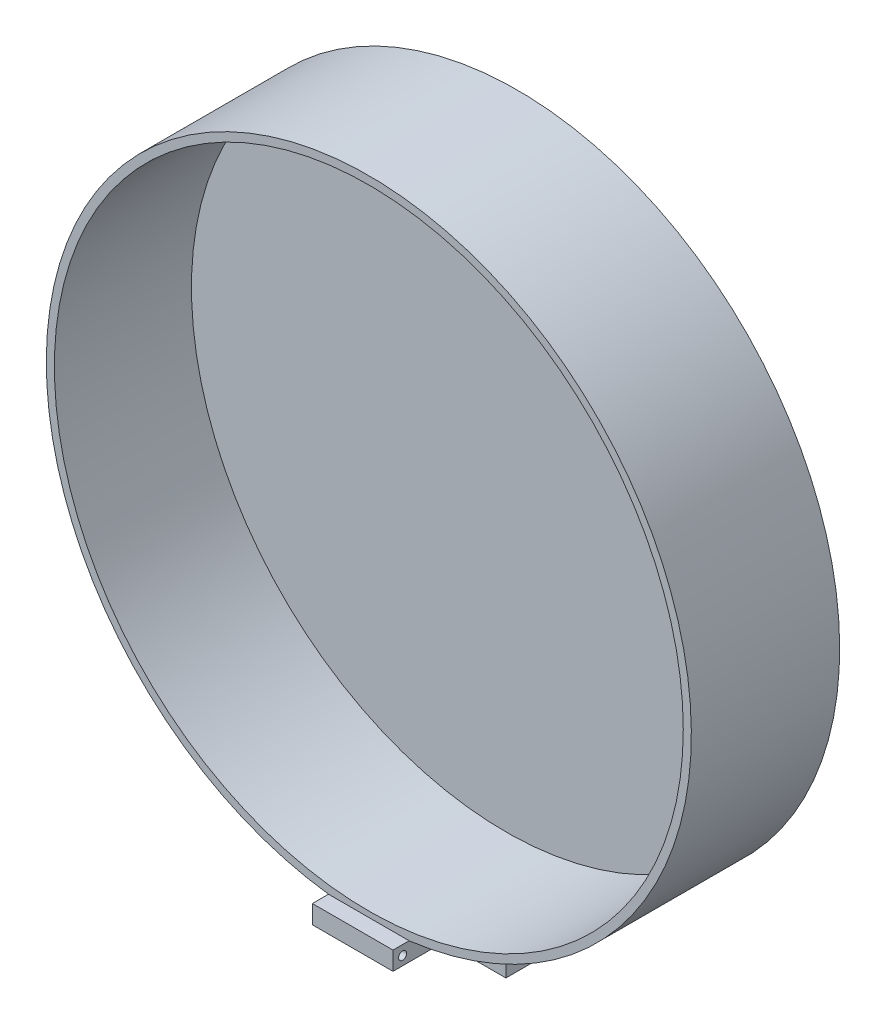
SolidWorks part; units mm, degrees
ref_plane "Front Plane" through (0, 0, 0) normal (0, 0, 1) x (1, 0, 0)
ref_plane "Top Plane" through (0, 0, 0) normal (0, 1, 0) x (1, 0, 0)
ref_plane "Right Plane" through (0, 0, 0) normal (1, 0, 0) x (0, 0, -1)
sketch "Sketch1" plane through (0, 0, 0) normal (0, 0, 1) x (1, 0, 0)
  line L0 (0, 0) -> (12.7, 0)
  line L1 (12.7, 0) -> (12.7, 12.7)
  line L2 (0, 0) -> (0, 12.7)
  arc A0 (0, 12.7) -> (12.7, 12.7) centre (6.35, 63.1016) cw
  dimension "D4" = 50.8
  dimension "D1" = 12.7
  dimension "D2" = 12.7
  dimension "D3" = 12.7
extrude "Boss-Extrude1" add sketch "Sketch1" along normal blind 23.368
sketch "Sketch4" plane through (0, 0, 23.368) normal (0, 0, 1) x (1, 0, 0)
  line L0 (-44.45, 63.1016) -> (57.15, 63.1016) construction
  arc A0 (12.7, 12.7) -> (0, 12.7) centre (6.35, 63.1016) ccw construction
  circle A1 centre (6.35, 63.1016) radius 49.53
  dimension "D1" = 99.06
extrude "Cut-Extrude1" cut sketch "Sketch4" against normal blind 21.59
sketch "Sketch5" plane through (0, 0, 23.368) normal (0, 0, 1) x (1, 0, 0)
  line L0 (0, 0) -> (12.7, 0)
  line L1 (12.7, 0) -> (12.7, 12.7)
  line L5 (0, 12.7) -> (0, 0)
  arc A2 (0, 12.7) -> (12.7, 12.7) centre (6.35, 63.1016) ccw
  dimension "D1" = 50.8
extrude "Cut-Extrude2" cut sketch "Sketch5" against normal blind 15.24
sketch "Sketch6" plane through (0, 0, 8.128) normal (0, 0, 1) x (1, 0, 0)
  line L0 (12.7, 9.7946) -> (0, 9.7946)
  line L1 (12.7, 0) -> (12.7, 12.7) construction
  line L2 (0, 12.7) -> (0, 0) construction
  line L3 (0, 9.7946) -> (0, 12.7)
  line L4 (12.7, 9.7946) -> (12.7, 12.7)
  arc A0 (12.7, 12.7) -> (0, 12.7) centre (6.35, 63.1016) cw
extrude "Boss-Extrude2" add sketch "Sketch6" along normal up to surface (15.24 mm away) up to face at (55.88, 63.1016, 23.368)
sketch "Sketch7" plane through (0, 0, 0) normal (-1, 0, 0) x (0, 0, 1)
  line L0 (23.368, 11.2473) -> (20.5438, 11.2473) construction
  line L1 (23.368, 9.7946) -> (23.368, 12.7) construction
  circle A0 centre (21.9559, 11.2473) radius 0.508
  dimension "D1" = 1.016
sketch "Sketch8" plane through (0, 0, 23.368) normal (0, 0, 1) x (1, 0, 0)
  line L0 (12.7, 12.7) -> (0, 12.7)
  line L1 (0, 12.7) -> (0, 9.7946)
  line L2 (0, 9.7946) -> (0, 12.7) construction
  line L3 (12.7, 9.7946) -> (0, 9.7946) construction
  line L4 (0, 9.7946) -> (12.7, 9.7946)
  line L5 (12.7, 12.7) -> (12.7, 9.7946) construction
  line L6 (12.7, 9.7946) -> (12.7, 12.7)
extrude "Boss-Extrude3" add sketch "Sketch8" along normal blind 2.54
sketch "Sketch9" plane through (0, 0, 0) normal (-1, 0, 0) x (0, 0, 1)
  line L0 (25.908, 11.1893) -> (22.8817, 11.1893) construction
  line L1 (25.908, 12.7) -> (25.908, 9.7946) construction
  circle A0 centre (24.3948, 11.1893) radius 0.635
  dimension "D1" = 1.27
extrude "Cut-Extrude4" cut sketch "Sketch9" against normal through all
